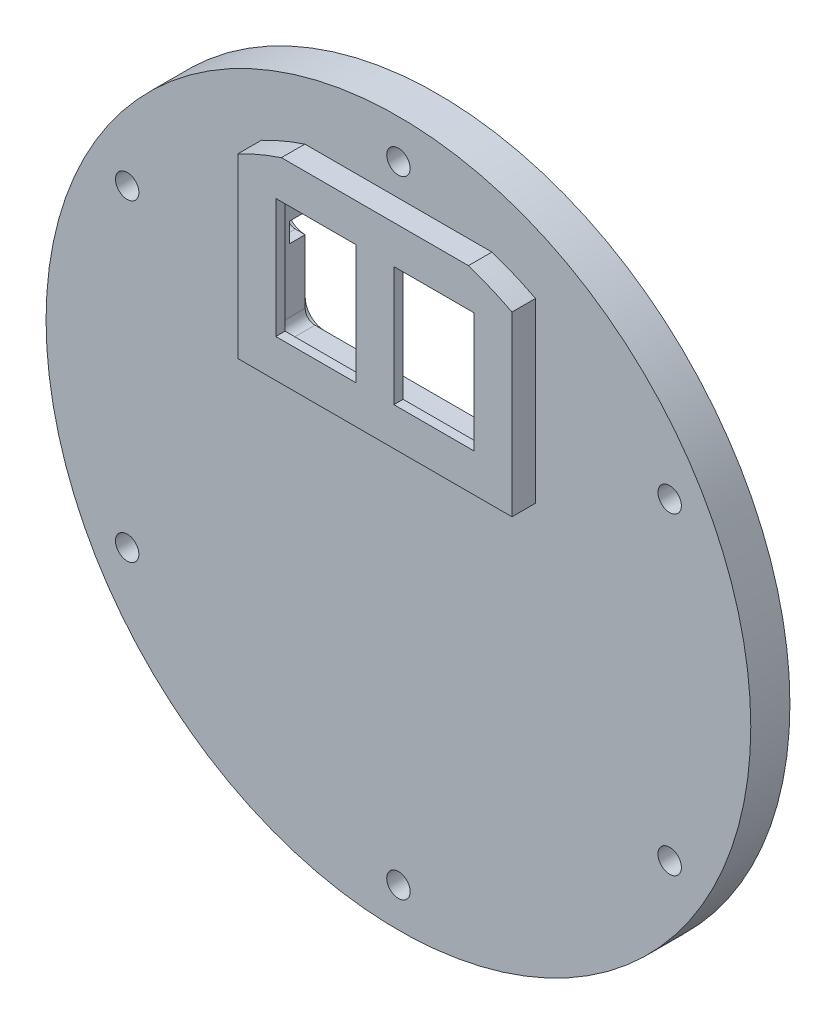
SolidWorks part; units mm, degrees
ref_plane "Front Plane" through (0, 0, 0) normal (0, 0, 1) x (1, 0, 0)
ref_plane "Top Plane" through (0, 0, 0) normal (0, 1, 0) x (1, 0, 0)
ref_plane "Right Plane" through (0, 0, 0) normal (1, 0, 0) x (0, 0, -1)
sketch "Sketch1" plane through (0, 0, 0) normal (0, 0, 1) x (1, 0, 0)
  circle A0 centre (0, 0) radius 57.15
  dimension "D1" = 114.3
extrude "Boss-Extrude1" add sketch "Sketch1" along normal blind 6.35
sketch "Sketch2" plane through (0, 0, 6.35) normal (0, 0, 1) x (1, 0, 0)
  line L0 (22.225, 13.9303) -> (22.225, 45.6803)
  line L1 (-22.225, 45.6803) -> (22.225, 45.6803)
  line L2 (-22.225, 45.6803) -> (-22.225, 13.9303)
  line L3 (-22.225, 13.9303) -> (22.225, 13.9303)
  line L9 (0, 13.9303) -> (0, 45.6803) construction
  line L10 (0, 0) -> (0, 57.15) construction
  circle A1 centre (0, 0) radius 57.15 construction
  circle A2 centre (0, 0) radius 50.8 construction
  dimension "D3" = 6.35
  dimension "D1" = 44.45
  dimension "D2" = 31.75
extrude "Boss-Extrude2" add sketch "Sketch2" along normal blind 3.81 contours L1 L0 L3 L2
sketch "Sketch3" plane through (0, 0, 10.16) normal (0, 0, 1) x (1, 0, 0)
  line L0 (0, 45.6803) -> (0, 13.9303) construction
  line L1 (-16.075, 39.5053) -> (-3.075, 39.5053)
  line L2 (-16.075, 39.5053) -> (-16.075, 20.1053)
  line L3 (-16.075, 20.1053) -> (-3.075, 20.1053)
  line L4 (-3.075, 39.5053) -> (-3.075, 20.1053)
  line L5 (3.075, 39.5053) -> (16.075, 39.5053)
  line L6 (3.075, 39.5053) -> (3.075, 20.1053)
  line L7 (3.075, 20.1053) -> (16.075, 20.1053)
  line L8 (16.075, 39.5053) -> (16.075, 20.1053)
  line L9 (-22.225, 45.6803) -> (22.225, 45.6803) construction
  line L10 (-22.225, 13.9303) -> (22.225, 13.9303) construction
  line L11 (-22.225, 29.8053) -> (-16.075, 29.8053) construction
  line L12 (-22.225, 45.6803) -> (-22.225, 13.9303) construction
  line L13 (16.075, 29.8053) -> (22.225, 29.8053) construction
  line L14 (22.225, 13.9303) -> (22.225, 45.6803) construction
  line L15 (-3.075, 29.8053) -> (3.075, 29.8053) construction
  dimension "D1" = 19.4
  dimension "D2" = 13
  dimension "D3" = 13
  dimension "D4" = 19.4
extrude "Cut-Extrude1" cut sketch "Sketch3" against normal through all
sketch "Sketch4" plane through (0, 0, 0) normal (0, 0, -1) x (-1, 0, 0)
  line L0 (16.075, 20.1053) -> (3.075, 20.1053) construction
  line L1 (-19.885, 43.3153) -> (19.885, 43.3153)
  line L2 (-19.885, 43.3153) -> (-19.885, 16.2953)
  line L3 (-19.885, 16.2953) -> (19.885, 16.2953)
  line L4 (19.885, 43.3153) -> (19.885, 16.2953)
  line L5 (3.075, 39.5053) -> (16.075, 39.5053) construction
  line L6 (16.075, 39.5053) -> (16.075, 20.1053) construction
  line L7 (-16.075, 20.1053) -> (-16.075, 39.5053) construction
  dimension "D1" = 3.81
  dimension "D2" = 3.81
  dimension "D3" = 3.81
  dimension "D4" = 3.81
extrude "Cut-Extrude2" cut sketch "Sketch4" against normal offset from surface (8.66 mm away) 1.5 up to face at (-9.575, 29.8053, 10.16)
fillet "Fillet1" radius 1.5875 4 edges at (19.885, 16.2953, 4.33) (-19.885, 16.2953, 4.33) (-19.885, 43.3153, 4.33) (19.885, 43.3153, 4.33)
sketch "Sketch8" plane through (0, 0, 0) normal (0, 0, -1) x (-1, 0, 0)
  line L0 (-19.885, 41.7278) -> (-19.885, 17.8828) construction
  line L1 (-18.2975, 16.2953) -> (18.2975, 16.2953) construction
  line L2 (19.885, 17.8828) -> (19.885, 41.7278) construction
  line L3 (18.2975, 43.3153) -> (-18.2975, 43.3153) construction
  line L4 (-19.885, 41.7278) -> (-19.885, 17.8828)
  line L5 (-18.2975, 16.2953) -> (18.2975, 16.2953)
  line L6 (19.885, 17.8828) -> (19.885, 41.7278)
  line L7 (18.2975, 43.3153) -> (-18.2975, 43.3153)
  line L8 (18.2975, 44.9028) -> (-18.2975, 44.9028)
  line L9 (-21.4725, 41.7278) -> (-21.4725, 17.8828) construction
  line L10 (-18.2975, 14.7078) -> (18.2975, 14.7078)
  line L11 (21.4725, 17.8828) -> (21.4725, 41.7278) construction
  line L12 (-21.4725, 32.9803) -> (-21.4725, 41.7278)
  line L13 (-21.4725, 26.6303) -> (-21.4725, 17.8828)
  line L14 (21.4725, 17.8828) -> (21.4725, 26.6303)
  line L15 (21.4725, 32.9803) -> (21.4725, 41.7278)
  arc A0 (-18.2975, 43.3153) -> (-19.885, 41.7278) centre (-18.2975, 41.7278) ccw construction
  circle A1 centre (0, 0) radius 57.15
  circle A2 centre (0, 0) radius 57.15
  arc A3 (-19.885, 17.8828) -> (-18.2975, 16.2953) centre (-18.2975, 17.8828) ccw construction
  arc A4 (18.2975, 16.2953) -> (19.885, 17.8828) centre (18.2975, 17.8828) ccw construction
  arc A5 (19.885, 41.7278) -> (18.2975, 43.3153) centre (18.2975, 41.7278) ccw construction
  arc A6 (-18.2975, 43.3153) -> (-19.885, 41.7278) centre (-18.2975, 41.7278) ccw
  arc A7 (-19.885, 17.8828) -> (-18.2975, 16.2953) centre (-18.2975, 17.8828) ccw
  arc A8 (18.2975, 16.2953) -> (19.885, 17.8828) centre (18.2975, 17.8828) ccw
  arc A9 (19.885, 41.7278) -> (18.2975, 43.3153) centre (18.2975, 41.7278) ccw
  arc A10 (-18.2975, 44.9028) -> (-21.4725, 41.7278) centre (-18.2975, 41.7278) ccw
  arc A11 (-21.4725, 17.8828) -> (-18.2975, 14.7078) centre (-18.2975, 17.8828) ccw
  arc A12 (18.2975, 14.7078) -> (21.4725, 17.8828) centre (18.2975, 17.8828) ccw
  arc A13 (21.4725, 41.7278) -> (18.2975, 44.9028) centre (18.2975, 41.7278) ccw
  arc A14 (21.4725, 26.6303) -> (21.4725, 32.9803) centre (21.4725, 29.8053) ccw
  arc A15 (-21.4725, 32.9803) -> (-21.4725, 26.6303) centre (-21.4725, 29.8053) ccw
  dimension "D3" = 6.35
  dimension "D4" = 6.35
  dimension "D1" = 0
  dimension "D2" = 1.5875
extrude "Cut-Extrude3" cut sketch "Sketch8" against normal blind 1.5875 contours L12 A10 L8 A13 L15 A14 L14 A12 L10 A11 L13 A15
hole_wizard "CBORE for #6 Pan Head Machine Screw1" positions "Sketch9" profile "Sketch10" counterbore size "#6" standard "ANSI Inch" end condition through all
sketch "Sketch9" plane through (0, 0, 0) normal (0, 0, -1) x (-1, 0, 0)
  line L0 (0, 0) -> (-43.9941, -25.4) construction
  line L2 (-43.9941, -25.4) -> (-49.4934, -28.575) construction
  line L3 (0, 0) -> (-57.15, 0) construction
  circle A1 centre (0, 0) radius 57.15 construction
  point P0 (-43.9941, -25.4)
  dimension "D1" = 50.8
  dimension "D2" = 30
sketch "Sketch10" plane through (43.9941, -25.4, 0) normal (1, 0, 0) x (0, 1, 0)
  line L0 (0, 0) -> (0, 10.16)
  line L1 (0, 10.16) -> (1.8986, 10.16)
  line L3 (1.8986, 10.16) -> (1.8987, 2.4638)
  line L4 (1.8987, 2.4638) -> (3.7706, 2.4638)
  line L5 (3.7706, 2.4638) -> (3.7706, 0)
  line L7 (3.7706, 0) -> (0, 0)
  line L11 (0, -6.35) -> (0, 107.95) construction
  dimension "Thru Hole Dia." = 3.7973
  dimension "Thru Hole Depth" = 10.16
  dimension "C'Bore Dia." = 7.5413
  dimension "C'Bore Depth" = 2.4638
pattern_circular "CirPattern1" count 6 over 360 about axis through (0, 0, 0) along (0, 0, 1) of "CBORE for #6 Pan Head Machine Screw1"
sketch "Sketch27" plane through (0, 0, 6.35) normal (0, 0, 1) x (1, 0, 0)
  circle A0 centre (0, 0) radius 48.133
  circle A1 centre (0, 0) radius 63.5
  dimension "D1" = 96.266
  dimension "D2" = 127
extrude "Cut-Extrude14" cut sketch "Sketch27" along normal through all
sketch "Sketch28" plane through (0, 0, 1.5875) normal (0, 0, -1) x (-1, 0, 0)
  line L0 (-21.4725, 31.3928) -> (-19.885, 31.3928)
  line L1 (-19.885, 17.8828) -> (-19.885, 41.7278) construction
  line L2 (-21.4725, 28.2178) -> (-19.885, 28.2178)
  line L4 (-19.885, 31.3928) -> (-19.885, 28.2178)
  line L5 (21.4725, 28.2178) -> (19.885, 28.2178)
  line L6 (21.4725, 31.3928) -> (19.885, 31.3928)
  line L7 (19.885, 41.7278) -> (19.885, 17.8828) construction
  line L8 (19.885, 31.3928) -> (19.885, 28.2178)
  arc A0 (-21.4725, 31.3928) -> (-21.4725, 28.2178) centre (-21.4725, 29.8053) ccw
  arc A1 (21.4725, 28.2178) -> (21.4725, 31.3928) centre (21.4725, 29.8053) ccw
  point P17 (19.885, 28.2178)
  dimension "D1" = 3.175
extrude "Cut-Extrude15" cut sketch "Sketch28" against normal blind 2.54
sketch "Sketch29" plane through (0, 0, 0) normal (0, 0, -1) x (-1, 0, 0)
  line L0 (21.4725, 32.9803) -> (21.4725, 41.7278) construction
  line L1 (21.4725, 17.8828) -> (21.4725, 26.6303) construction
  line L2 (-18.2975, 14.7078) -> (18.2975, 14.7078) construction
  line L3 (-21.4725, 26.6303) -> (-21.4725, 17.8828) construction
  line L4 (-21.4725, 32.9803) -> (-21.4725, 41.7278) construction
  line L5 (18.2975, 44.9028) -> (-18.2975, 44.9028) construction
  line L6 (21.4725, 32.9803) -> (21.4725, 41.7278)
  line L7 (21.4725, 17.8828) -> (21.4725, 26.6303)
  line L8 (-18.2975, 14.7078) -> (18.2975, 14.7078)
  line L9 (-21.4725, 26.6303) -> (-21.4725, 17.8828)
  line L10 (-21.4725, 32.9803) -> (-21.4725, 41.7278)
  line L11 (18.2975, 44.9028) -> (-18.2975, 44.9028)
  arc A0 (21.4725, 41.7278) -> (18.2975, 44.9028) centre (18.2975, 41.7278) ccw construction
  arc A1 (21.4725, 26.6303) -> (21.4725, 32.9803) centre (21.4725, 29.8053) ccw construction
  arc A2 (18.2975, 14.7078) -> (21.4725, 17.8828) centre (18.2975, 17.8828) ccw construction
  arc A3 (-21.4725, 17.8828) -> (-18.2975, 14.7078) centre (-18.2975, 17.8828) ccw construction
  arc A4 (-21.4725, 32.9803) -> (-21.4725, 26.6303) centre (-21.4725, 29.8053) ccw construction
  arc A5 (-18.2975, 44.9028) -> (-21.4725, 41.7278) centre (-18.2975, 41.7278) ccw construction
  arc A6 (21.4725, 41.7278) -> (18.2975, 44.9028) centre (18.2975, 41.7278) ccw
  arc A7 (21.4725, 26.6303) -> (21.4725, 32.9803) centre (21.4725, 29.8053) ccw
  arc A8 (18.2975, 14.7078) -> (21.4725, 17.8828) centre (18.2975, 17.8828) ccw
  arc A9 (-21.4725, 17.8828) -> (-18.2975, 14.7078) centre (-18.2975, 17.8828) ccw
  arc A10 (-21.4725, 32.9803) -> (-21.4725, 26.6303) centre (-21.4725, 29.8053) ccw
  arc A11 (-18.2975, 44.9028) -> (-21.4725, 41.7278) centre (-18.2975, 41.7278) ccw
